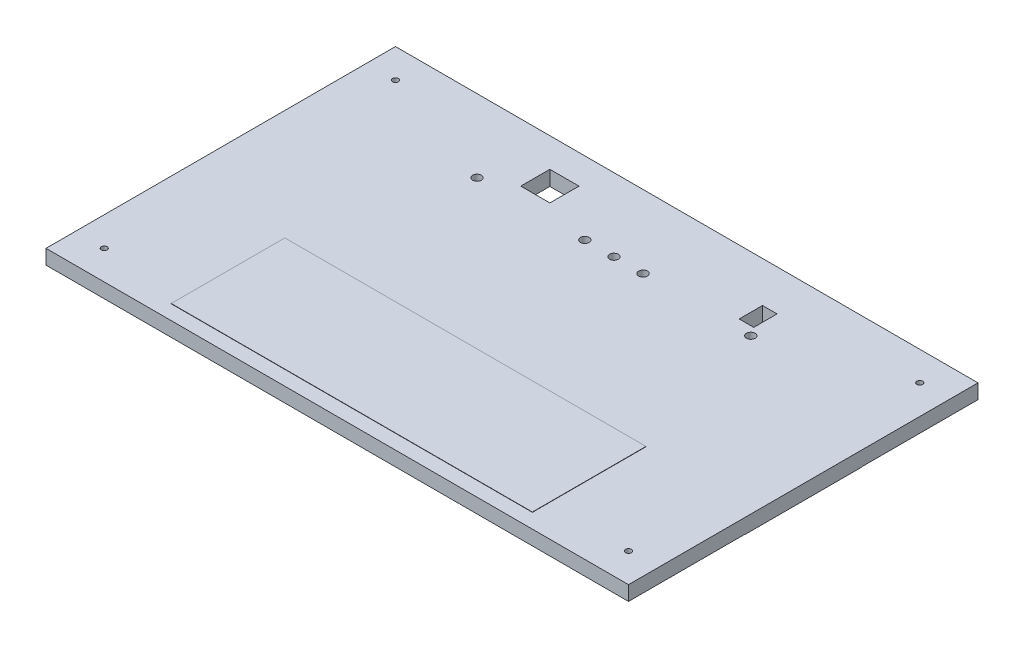
SolidWorks part; units mm, degrees
ref_plane "Front Plane" through (0, 0, 0) normal (0, 0, 1) x (1, 0, 0)
ref_plane "Top Plane" through (0, 0, 0) normal (0, 1, 0) x (1, 0, 0)
ref_plane "Right Plane" through (0, 0, 0) normal (1, 0, 0) x (0, 0, -1)
sketch "Sketch1" plane through (0, 0, 0) normal (0, 1, 0) x (1, 0, 0)
  line L0 (0, 0) -> (0, 120)
  line L1 (0, 120) -> (200, 120)
  line L2 (200, 120) -> (200, 0)
  line L3 (200, 0) -> (0, 0)
  dimension "D1" = 200
  dimension "D2" = 120
extrude "Boss-Extrude1" add sketch "Sketch1" along normal blind 5
sketch "Sketch2" plane through (0, 5, 0) normal (0, 1, 0) x (1, 0, 0)
  line L0 (0, 120) -> (0, 0) construction
  line L1 (200, 120) -> (0, 120) construction
  line L2 (100, 120) -> (100, 88.5569) construction
  line L3 (0, 60) -> (36.4204, 60) construction
  circle A0 centre (10, 110) radius 1
  circle A1 centre (190, 110) radius 1
  circle A2 centre (190, 10) radius 1
  circle A3 centre (10, 10) radius 1
  dimension "D1" = 10
  dimension "D3" = 2
  dimension "D2" = 10
extrude "Cut-Extrude1" cut sketch "Sketch2" against normal blind 10
sketch "Sketch3" plane through (0, 0, 0) normal (0, -1, 0) x (1, 0, 0)
  line L0 (0, -40) -> (27, -40)
  line L1 (0, -120) -> (0, 0) construction
  line L2 (27, -40) -> (27, -80)
  line L3 (27, -80) -> (0, -80)
  line L4 (0, -80) -> (0, -40)
  line L5 (200, 0) -> (200, -120) construction
  line L6 (100, 0) -> (100, -29.9106) construction
  line L7 (0, 0) -> (200, 0) construction
  line L8 (173, -80) -> (200, -80)
  line L9 (173, -40) -> (173, -80)
  line L10 (200, -40) -> (173, -40)
  line L11 (200, -80) -> (200, -40)
  point P6 (27, -60)
  point P9 (200, -60)
  dimension "D1" = 27
  dimension "D2" = 40
  dimension "D3" = 0
extrude "Boss-Extrude2" add sketch "Sketch3" along normal blind 0.1
sketch "Sketch4" plane through (0, 0, 0) normal (0, -1, 0) x (1, 0, 0)
  line L1 (50, -92) -> (150, -92)
  line L2 (50, -92) -> (50, -120)
  line L3 (50, -120) -> (150, -120)
  line L4 (150, -92) -> (150, -120)
  line L5 (200, -120) -> (0, -120) construction
  point P6 (100, -120)
  point P7 (100, -120)
  dimension "D1" = 28
  dimension "D2" = 100
  dimension "D3" = 28
extrude "Boss-Extrude3" add sketch "Sketch4" along normal blind 0.1
sketch "Sketch5" plane through (0, -0.1, 0) normal (0, -1, 0) x (1, 0, 0)
  line L0 (50, -92) -> (50, -120) construction
  line L1 (150, -92) -> (50, -92) construction
  line L2 (150, -120) -> (150, -92) construction
  line L3 (100, -95) -> (100, -107.7231) construction
  line L12 (145, -98) -> (145, -106)
  line L13 (145, -106) -> (140, -106)
  line L14 (140, -106) -> (140, -98)
  line L15 (140, -98) -> (145, -98)
  line L17 (50, -120) -> (150, -120) construction
  line L19 (63, -100) -> (73, -100)
  line L20 (63, -100) -> (63, -110)
  line L21 (63, -110) -> (73, -110)
  line L22 (73, -100) -> (73, -110)
  circle A0 centre (53, -95) radius 1.5
  circle A1 centre (90, -95) radius 1.5
  circle A2 centre (100, -95) radius 1.5
  circle A3 centre (110, -95) radius 1.5
  circle A4 centre (147, -95) radius 1.5
  dimension "D1" = 3
  dimension "D2" = 3
  dimension "D3" = 3
  dimension "D4" = 40
  dimension "D5" = 10
  dimension "D6" = 10
  dimension "D7" = 3
  dimension "D8" = 5
  dimension "D9" = 8
  dimension "D10" = 5
  dimension "D11" = 14
  dimension "D12" = 10
  dimension "D13" = 10
  dimension "D14" = 13
  dimension "D15" = 10
extrude "Cut-Extrude2" cut sketch "Sketch5" against normal through all
sketch "Sketch6" plane through (0, 5, 0) normal (0, 1, 0) x (1, 0, 0)
  line L0 (200, 120) -> (0, 120) construction
  line L1 (38, 44) -> (162, 44)
  line L2 (38, 44) -> (38, 5)
  line L3 (38, 5) -> (162, 5)
  line L4 (162, 44) -> (162, 5)
  line L5 (0, 0) -> (200, 0) construction
  point P6 (100, 120)
  point P7 (100, 44)
  dimension "D1" = 124
  dimension "D2" = 39
  dimension "D3" = 5
extrude "Boss-Extrude4" add sketch "Sketch6" along normal blind 0.1
